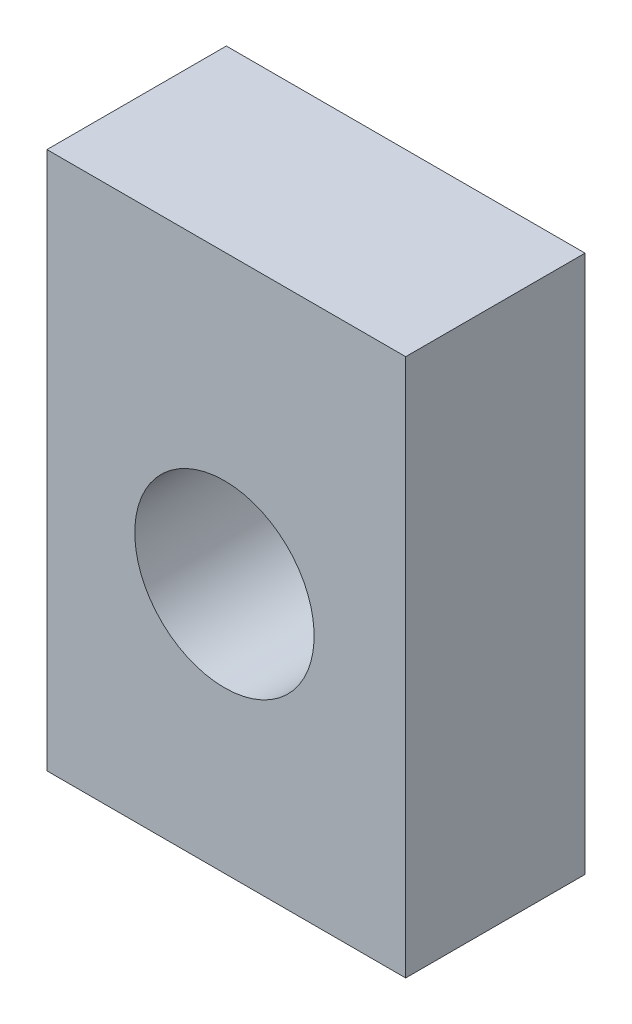
SolidWorks part; units mm, degrees
ref_plane "Front Plane" through (0, 0, 0) normal (0, 0, 1) x (1, 0, 0)
ref_plane "Top Plane" through (0, 0, 0) normal (0, 1, 0) x (1, 0, 0)
ref_plane "Right Plane" through (0, 0, 0) normal (1, 0, 0) x (0, 0, -1)
sketch "Sketch1" plane through (0, 0, 0) normal (1, 0, 0) x (0, 0, -1)
  line L1 (-3.175, 9.525) -> (3.175, 9.525)
  line L2 (-3.175, 9.525) -> (-3.175, -9.525)
  line L3 (-3.175, -9.525) -> (3.175, -9.525)
  line L4 (3.175, 9.525) -> (3.175, -9.525)
  line L5 (-3.175, 9.525) -> (3.175, -9.525) construction
  line L6 (-3.175, -9.525) -> (3.175, 9.525) construction
  point P0 (0, 0)
  dimension "D1" = 19.05
  dimension "D2" = 6.35
extrude "Boss-Extrude1" add sketch "Sketch1" along normal blind 12.7
sketch "Sketch2" plane through (0, 0, -3.175) normal (0, 0, -1) x (-1, 0, 0)
  circle A0 centre (-6.2841, -0.6594) radius 3.175
  point P2 (-6.2841, -0.6594)
  dimension "D1" = 6.35
extrude "Cut-Extrude1" cut sketch "Sketch2" against normal blind 12.7
